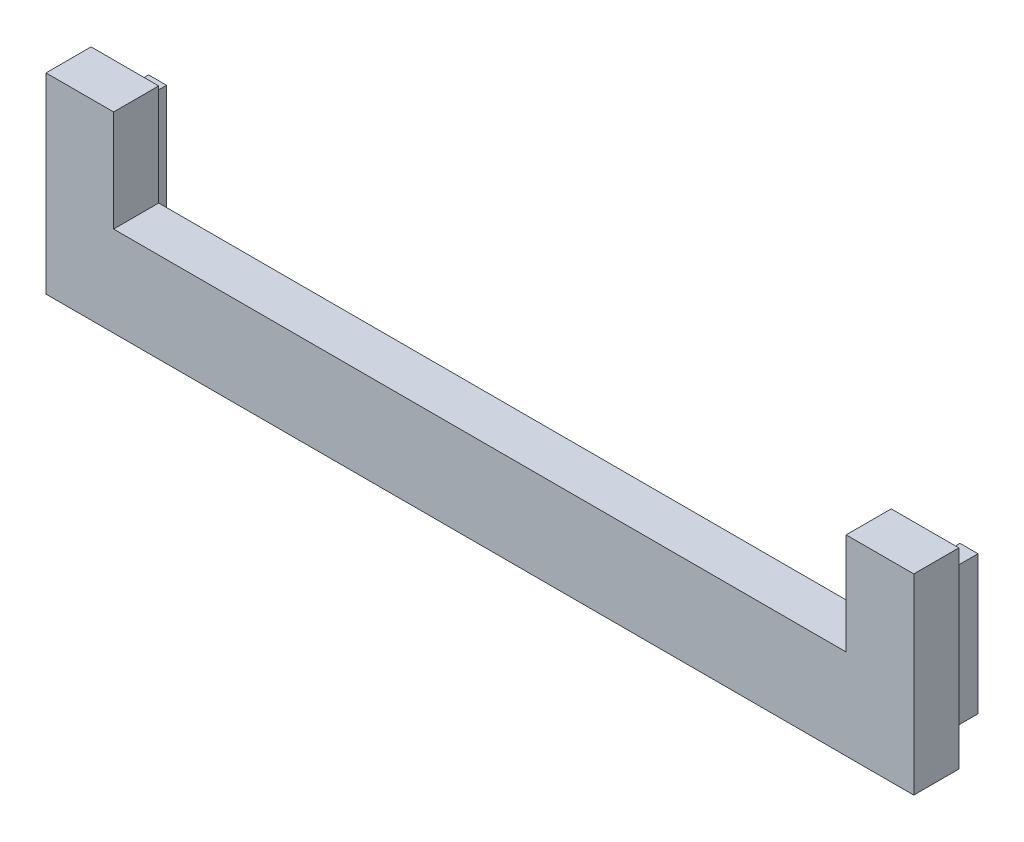
SolidWorks part; units mm, degrees
ref_plane "Front Plane" through (0, 0, 0) normal (0, 0, 1) x (1, 0, 0)
ref_plane "Top Plane" through (0, 0, 0) normal (0, 1, 0) x (1, 0, 0)
ref_plane "Right Plane" through (0, 0, 0) normal (1, 0, 0) x (0, 0, -1)
sketch "Sketch1" plane through (0, 0, 0) normal (0, 0, 1) x (1, 0, 0)
  line L1 (-19.25, 4.25) -> (19.25, 4.25)
  line L2 (-19.25, 4.25) -> (-19.25, -4.25)
  line L3 (-19.25, -4.25) -> (19.25, -4.25)
  line L4 (19.25, 4.25) -> (19.25, -4.25)
  point P4 (0, -4.25)
  point P6 (19.25, 0)
  dimension "D1" = 8.5
  dimension "D2" = 38.5
extrude "Boss-Extrude1" add sketch "Sketch1" along normal blind 2 contours L1 L4 L3 L2
sketch "Sketch2" plane through (0, 0, 0) normal (0, 0, -1) x (-1, 0, 0)
  line L0 (19.25, 4.25) -> (-19.25, 4.25) construction
  line L1 (-18.4, 2.75) -> (-17.6, 2.75)
  line L2 (-18.4, 2.75) -> (-18.4, -3.4)
  line L4 (-17.6, 2.75) -> (-17.6, -3.4)
  line L10 (-19.25, 4.25) -> (-19.25, -4.25) construction
  line L11 (-18.4, -3.4) -> (-17.6, -3.4)
  line L12 (19.25, -4.25) -> (-19.25, -4.25) construction
  dimension "D1" = 0.8
  dimension "D2" = 0.85
  dimension "D3" = 1.5
  dimension "D5" = 0.85
extrude "Boss-Extrude2" add sketch "Sketch2" along normal blind 1.7
mirror "Mirror1" about plane through (0, 0, 0) normal (1, 0, 0) of "Boss-Extrude2"
sketch "Sketch3" plane through (0, 0, 2) normal (0, 0, 1) x (1, 0, 0)
  line L0 (-19.25, 4.25) -> (19.25, 4.25) construction
  line L1 (-16.25, 4.25) -> (16.25, 4.25)
  line L2 (-16.25, 4.25) -> (-16.25, -0.25)
  line L3 (-16.25, -0.25) -> (16.25, -0.25)
  line L4 (16.25, 4.25) -> (16.25, -0.25)
  line L5 (-19.25, 4.25) -> (-19.25, -4.25) construction
  line L6 (-19.25, -4.25) -> (19.25, -4.25) construction
  point P6 (0, -0.25)
  dimension "D1" = 3
  dimension "D2" = 4
extrude "Cut-Extrude1" cut sketch "Sketch3" against normal through all
